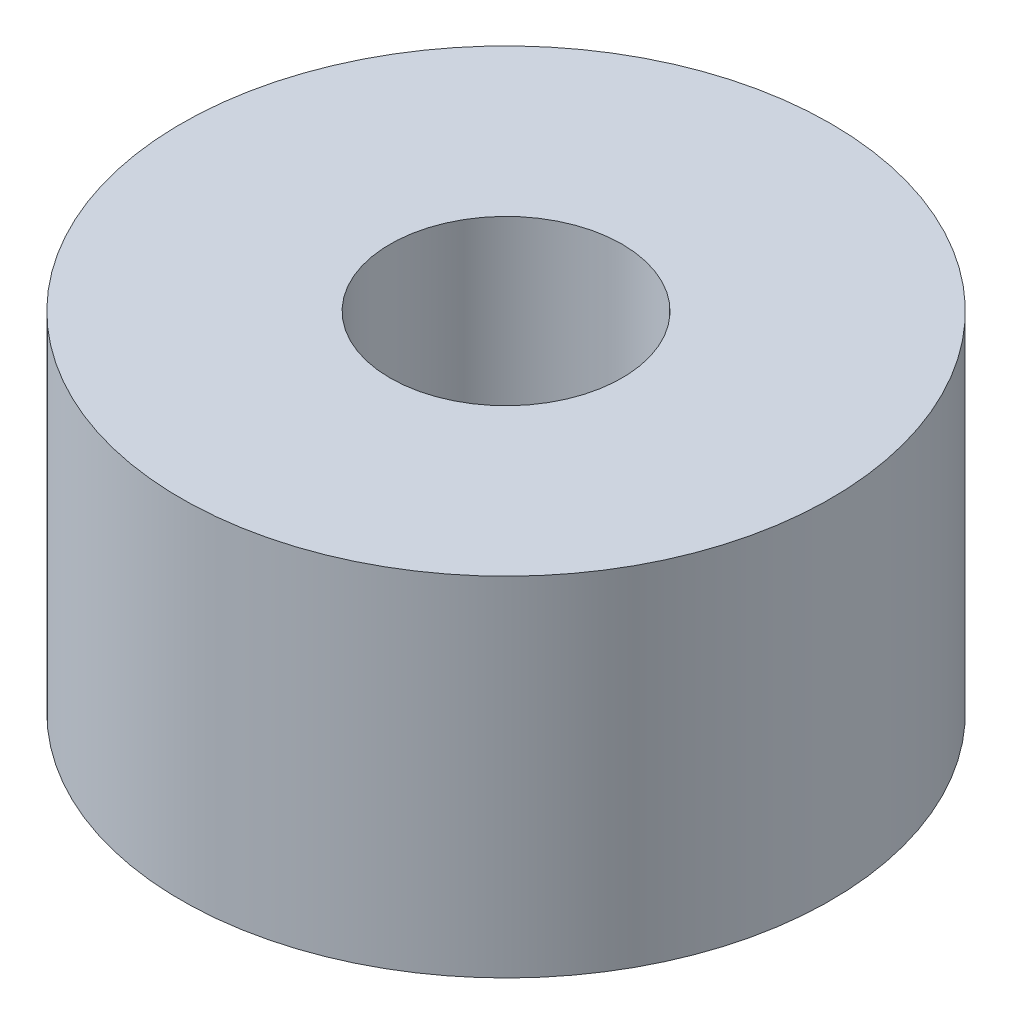
SolidWorks part; units mm, degrees
ref_plane "Front Plane" through (0, 0, 0) normal (0, 0, 1) x (1, 0, 0)
ref_plane "Top Plane" through (0, 0, 0) normal (0, 1, 0) x (1, 0, 0)
ref_plane "Right Plane" through (0, 0, 0) normal (1, 0, 0) x (0, 0, -1)
sketch "Sketch1" plane through (0, 0, 0) normal (0, 1, 0) x (1, 0, 0)
  circle A0 centre (0, 0) radius 8.89
  circle A1 centre (0, 0) radius 3.175
  dimension "D1" = 17.78
  dimension "D2" = 6.35
extrude "Boss-Extrude1" add sketch "Sketch1" along normal blind 9.525
